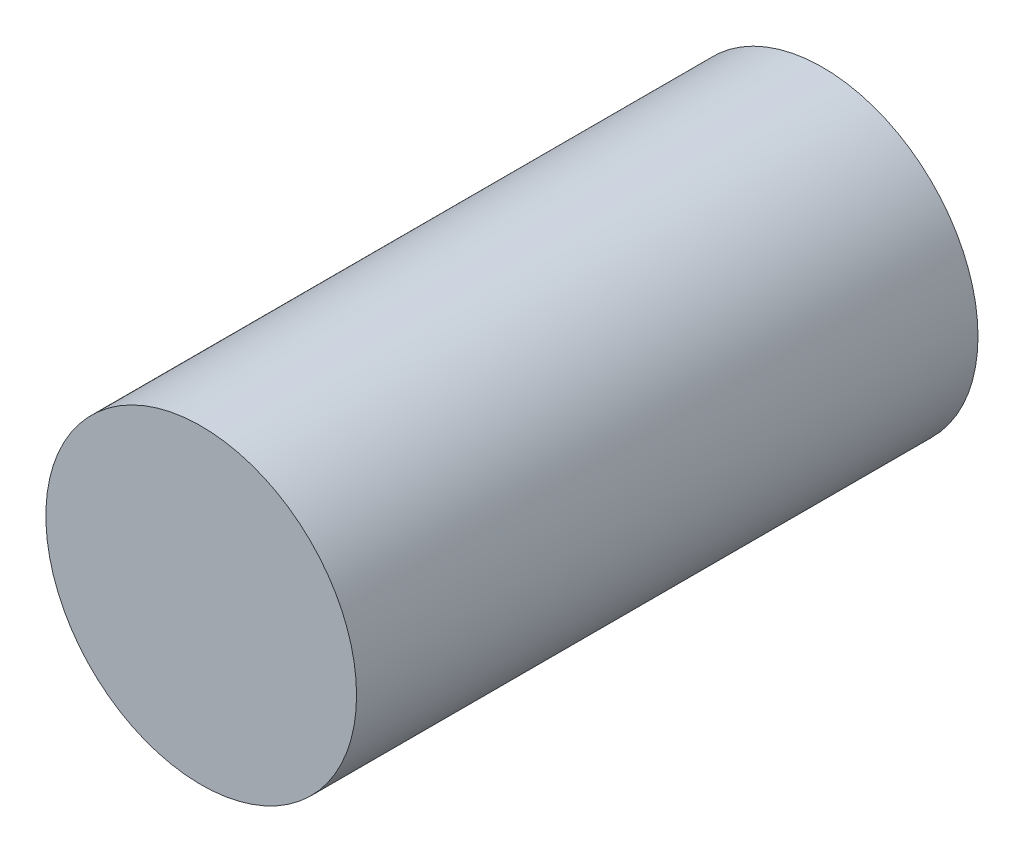
SolidWorks part; units mm, degrees
ref_plane "Alzado" through (0, 0, 0) normal (0, 0, 1) x (1, 0, 0)
ref_plane "Planta" through (0, 0, 0) normal (0, 1, 0) x (1, 0, 0)
ref_plane "Vista lateral" through (0, 0, 0) normal (1, 0, 0) x (0, 0, -1)
sketch "Croquis1" plane through (0, 0, 0) normal (0, 0, 1) x (1, 0, 0)
  circle A0 centre (0, 0) radius 1
  dimension "D1" = 2
extrude "Saliente-Extruir1" add sketch "Croquis1" along normal blind 4
